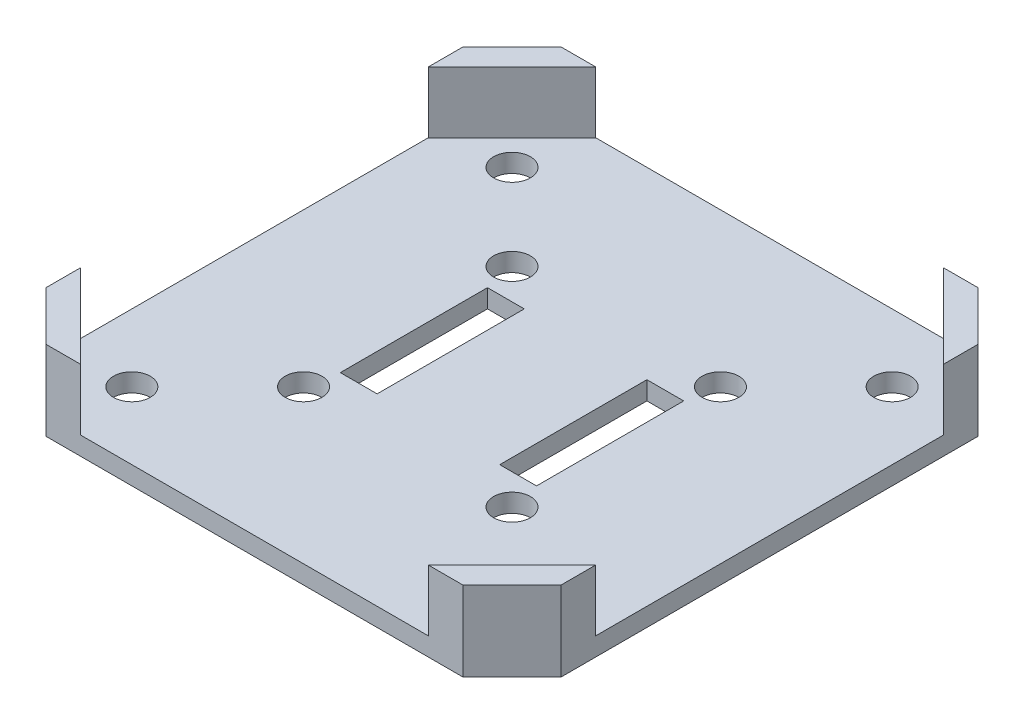
SolidWorks part; units mm, degrees
ref_plane "Front Plane" through (0, 0, 0) normal (0, 0, 1) x (1, 0, 0)
ref_plane "Top Plane" through (0, 0, 0) normal (0, 1, 0) x (1, 0, 0)
ref_plane "Right Plane" through (0, 0, 0) normal (1, 0, 0) x (0, 0, -1)
sketch "Sketch1" plane through (0, 0, 0) normal (0, 1, 0) x (1, 0, 0)
  line L0 (-21, 11.5) -> (-21, 17)
  line L1 (-17, 21) -> (17, 21)
  line L2 (21, 17) -> (21, 11.5)
  line L4 (11.5, 11.5) -> (11.5, -11.5) construction
  line L6 (21, -11.5) -> (21, -17)
  line L7 (17, -21) -> (-17, -21)
  line L8 (-21, -17) -> (-21, -11.5)
  line L10 (-11.5, -11.5) -> (-11.5, 11.5) construction
  line L12 (0, 0) -> (0, 21.7938) construction
  line L13 (-38.9691, 0) -> (38.9691, 0) construction
  line L14 (-21, -11.5) -> (-21, 11.5)
  line L15 (21, 11.5) -> (21, -11.5)
  line L16 (-21, 17) -> (-17, 21)
  line L17 (-11.5, 11.5) -> (11.5, 11.5) construction
  line L18 (-11.5, 11.5) -> (-11.5, -11.5) construction
  line L19 (-11.5, -11.5) -> (11.5, -11.5) construction
  line L20 (11.5, 11.5) -> (11.5, -11.5) construction
  line L21 (17, 21) -> (21, 17)
  line L23 (17, -21) -> (21, -17)
  line L24 (-17, -21) -> (-21, -17)
  circle A0 centre (-15.5, 15.5) radius 1.5
  circle A1 centre (15.5, 15.5) radius 1.5
  circle A2 centre (15.5, -15.5) radius 1.5
  circle A3 centre (-15.5, -15.5) radius 1.5
  circle A4 centre (-8.5, 8.5) radius 1.5
  circle A5 centre (8.5, 8.5) radius 1.5
  circle A6 centre (8.5, -8.5) radius 1.5
  circle A7 centre (-8.5, -8.5) radius 1.5
  point P18 (0, 0)
  point P40 (-21, -21)
  point P43 (21, -21)
  point P46 (21, 21)
  point P49 (-21, 21)
  dimension "D12" = 31
  dimension "D5" = 17
  dimension "D1" = 42
  dimension "D3" = 42
  dimension "D4" = 31
  dimension "D6" = 17
  dimension "D13" = 23
  dimension "D14" = 23
extrude "Boss-Extrude1" add sketch "Sketch1" along normal blind 1.5
sketch "Sketch2" plane through (0, 1.5, 0) normal (0, 1, 0) x (1, 0, 0)
  line L5 (-21, 17) -> (-17, 21)
  line L6 (21, 17) -> (17, 21)
  line L12 (0, 7.0817) -> (0, -7.0817) construction
  line L13 (-9.3787, 0) -> (9.3787, 0) construction
  line L21 (-17, -21) -> (-21, -17)
  line L23 (17, -21) -> (21, -17)
  line L24 (-19.5858, 15.5858) -> (-15.5858, 19.5858)
  line L25 (-15.5858, -19.5858) -> (-19.5858, -15.5858)
  line L31 (-21, 14.1716) -> (-21, 17)
  line L33 (-21, 14.1716) -> (-14.1716, 21)
  line L34 (-17, 21) -> (17, 21) construction
  line L35 (-21, -14.1716) -> (-14.1716, -21)
  line L36 (17, -21) -> (-17, -21) construction
  line L37 (-17, 21) -> (-14.1716, 21)
  line L38 (-17, -21) -> (-14.1716, -21)
  line L39 (-21, -17) -> (-21, -14.1716)
  line L40 (21, -14.1716) -> (14.1716, -21)
  line L41 (21, -17) -> (21, -14.1716)
  line L42 (17, -21) -> (21, -17)
  line L43 (17, -21) -> (14.1716, -21)
  line L44 (21, 14.1716) -> (21, 17)
  line L45 (17, 21) -> (14.1716, 21)
  line L46 (21, 17) -> (17, 21)
  line L47 (21, 14.1716) -> (14.1716, 21)
  line L48 (19.5858, 15.5858) -> (15.5858, 19.5858)
  line L49 (21, 14.1716) -> (14.1716, 21)
  line L50 (17, 21) -> (21, 17)
  line L51 (14.1716, -21) -> (17, -21)
  line L52 (21, -17) -> (21, -14.1716)
  line L53 (-14.1716, -21) -> (-17, -21)
  line L54 (-21, -17) -> (-21, -14.1716)
  line L55 (-21, -17) -> (-17, -21)
  line L56 (-14.1716, -21) -> (-21, -14.1716)
  line L57 (21, -17) -> (21, -14.1716)
  line L58 (14.1716, 21) -> (17, 21)
  line L59 (21, 14.1716) -> (21, 17)
  point P0 (0, 0)
  point P19 (-17.5858, 17.5858)
  point P24 (-17.5858, -17.5858)
  point P37 (0, 0)
  point P40 (0, 0)
  line M23 (-21, 17) -> (-21, -17)
  line M25 (-17, -21) -> (17, -21)
  line M27 (21, -17) -> (21, 17)
  line M29 (17, 21) -> (-17, 21)
  line M51 (-21, -17) -> (-17, -21)
  line M52 (17, -21) -> (21, -17)
  line M53 (21, 17) -> (17, 21)
  line M54 (-17, 21) -> (-21, 17)
  dimension "D1" = 2
sketch "Sketch3" plane through (0, 0, 0) normal (0, -1, 0) x (1, 0, 0)
  line L0 (0, 0) -> (0, -8.1) construction
  line L13 (5, 6) -> (8, 6)
  line L14 (-5, -6) -> (-8, -6)
  line L16 (-5, 6) -> (-8, 6)
  line L17 (-8, -6) -> (-8, 6)
  line L18 (8, -6) -> (8, 6)
  line L19 (5, -6) -> (8, -6)
  line L20 (5, -6) -> (5, 6)
  line L21 (-5, -6) -> (-5, 6)
  point P0 (-6.5, 6)
  dimension "D1" = 12
  dimension "D2" = 6.5
  dimension "D5" = 3
extrude "Cut-Extrude1" cut sketch "Sketch3" against normal blind 2
extrude "Boss-Extrude3" add sketch "Sketch2" along normal blind 5 contours L47 M27 M53 M29 | L33 L24 M23 M29 M54 | L35 L25 M23 M51 M25 | L40 M27 M25 M52
